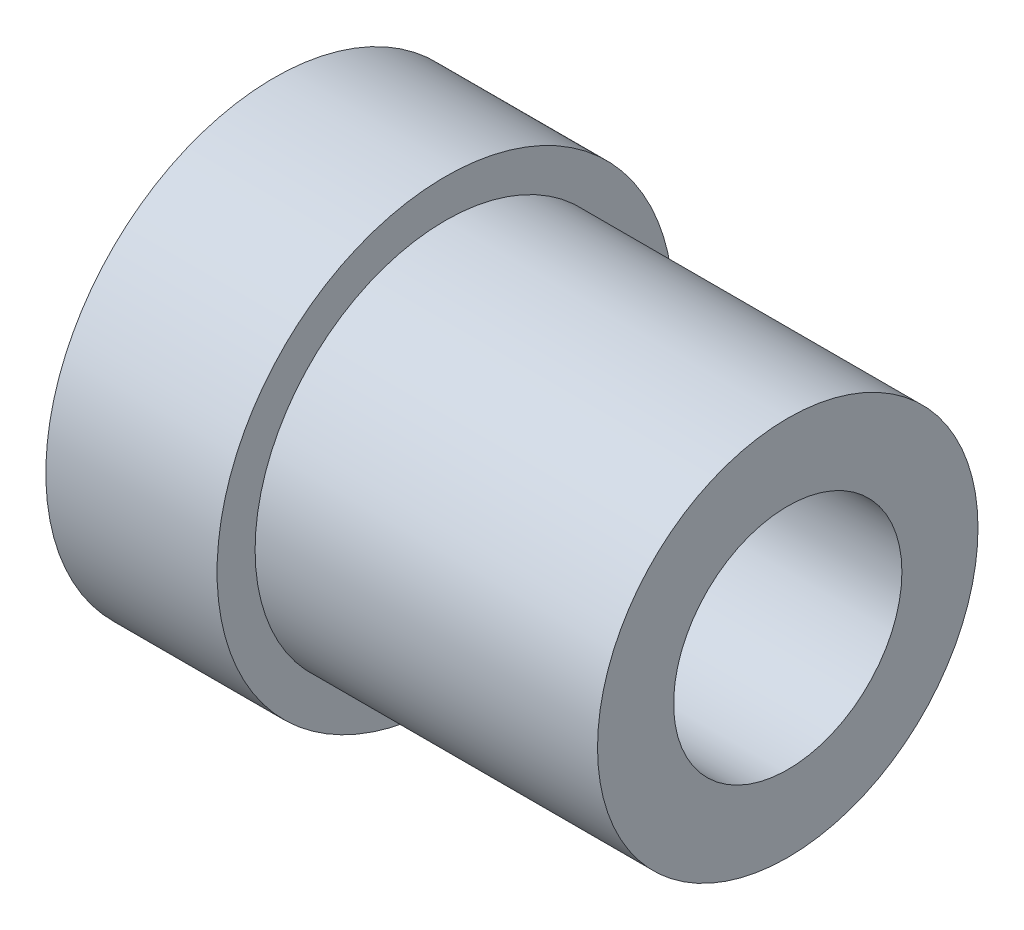
SolidWorks part; units mm, degrees
ref_plane "Front Plane" through (0, 0, 0) normal (0, 0, 1) x (1, 0, 0)
ref_plane "Top Plane" through (0, 0, 0) normal (0, 1, 0) x (1, 0, 0)
ref_plane "Right Plane" through (0, 0, 0) normal (1, 0, 0) x (0, 0, -1)
sketch "Sketch1" plane through (0, 0, 0) normal (1, 0, 0) x (0, 0, -1)
  circle A0 centre (0, 0) radius 6
  circle A1 centre (0, 0) radius 3
  dimension "D1" = 6
  dimension "D2" = 12
extrude "Boss-Extrude1" add sketch "Sketch1" along normal blind 4.5
sketch "Sketch2" plane through (4.5, 0, 0) normal (1, 0, 0) x (0, 0, -1)
  circle A0 centre (0, 0) radius 3 construction
  circle A1 centre (0, 0) radius 3
  circle A2 centre (0, 0) radius 5
  dimension "D1" = 10
extrude "Boss-Extrude2" add sketch "Sketch2" along normal blind 9
